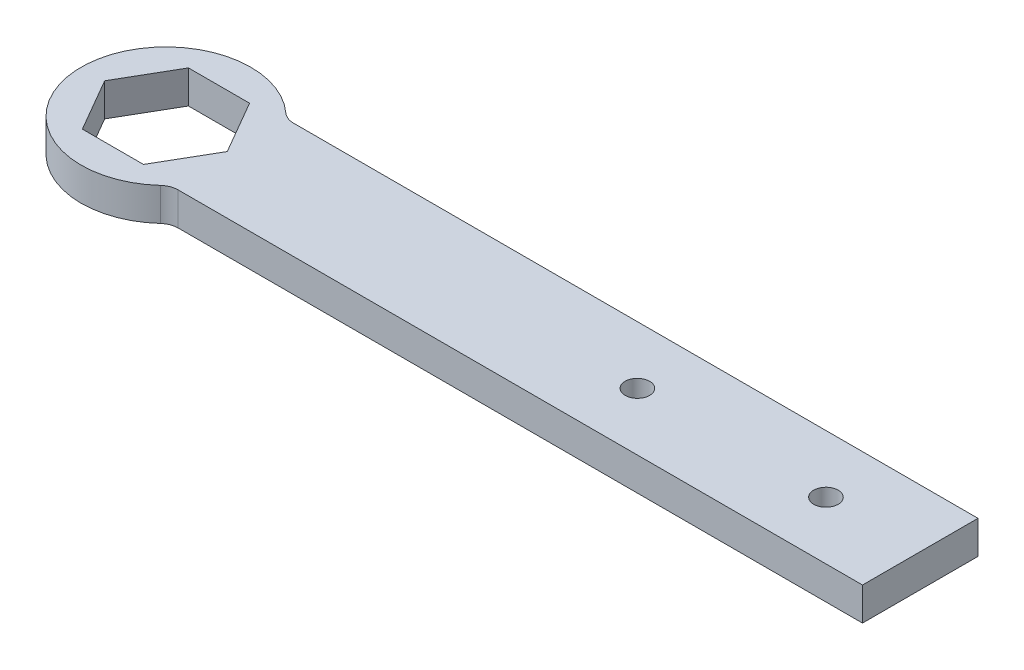
SolidWorks part; units mm, degrees
ref_plane "Front Plane" through (0, 0, 0) normal (0, 0, 1) x (1, 0, 0)
ref_plane "Top Plane" through (0, 0, 0) normal (0, 1, 0) x (1, 0, 0)
ref_plane "Right Plane" through (0, 0, 0) normal (1, 0, 0) x (0, 0, -1)
sketch "Sketch1" plane through (0, 0, 0) normal (0, 1, 0) x (1, 0, 0)
  line L0 (0, 0) -> (8.2367, 0)
  line L1 (8.2367, 0) -> (12.3734, -7.1437)
  line L2 (12.3734, -7.1437) -> (8.2367, -14.2875)
  line L3 (8.2367, -14.2875) -> (0, -14.2875)
  line L4 (0, -14.2875) -> (-4.1366, -7.1437)
  line L5 (-4.1366, -7.1437) -> (0, 0)
  line L6 (4.1184, 0) -> (4.1184, -14.2875) construction
  line L7 (-4.1366, -7.1437) -> (12.3734, -7.1437) construction
  line L12 (13.5356, 0.635) -> (105.7184, 0.635)
  line L13 (105.7184, 0.635) -> (105.7184, -14.9225)
  line L14 (105.7184, -14.9225) -> (13.5356, -14.9225)
  arc A0 (11.8234, 1.2989) -> (11.8234, -15.5864) centre (4.1184, -7.1437) ccw
  arc A1 (13.5356, -14.9225) -> (11.8234, -15.5864) centre (13.5356, -17.4625) ccw
  arc A2 (11.8234, 1.2989) -> (13.5356, 0.635) centre (13.5356, 3.175) ccw
  point P10 (4.1184, -7.1437)
  point P13 (12.4931, -14.9225)
  point P20 (12.4931, 0.635)
  dimension "D4" = 22.86
  dimension "D5" = 2.54
  dimension "D1" = 14.2875
  dimension "D2" = 16.51
  dimension "D3" = 14.2875
  dimension "D6" = 15.5575
  dimension "D7" = 101.6
extrude "Boss-Extrude1" add sketch "Sketch1" along normal blind 4.445
sketch "Sketch2" plane through (0, 4.445, 0) normal (0, 1, 0) x (1, 0, 0)
  line L0 (105.7184, -7.1438) -> (4.1184, -7.1437) construction
  line L1 (105.7184, -14.9225) -> (105.7184, 0.635) construction
  circle A0 centre (93.0184, -7.1437) radius 1.651
  circle A1 centre (67.6184, -7.1437) radius 1.651
  dimension "D2" = 25.4
  dimension "D3" = 3.302
  dimension "D1" = 63.5
extrude "Cut-Extrude1" cut sketch "Sketch2" against normal through all
